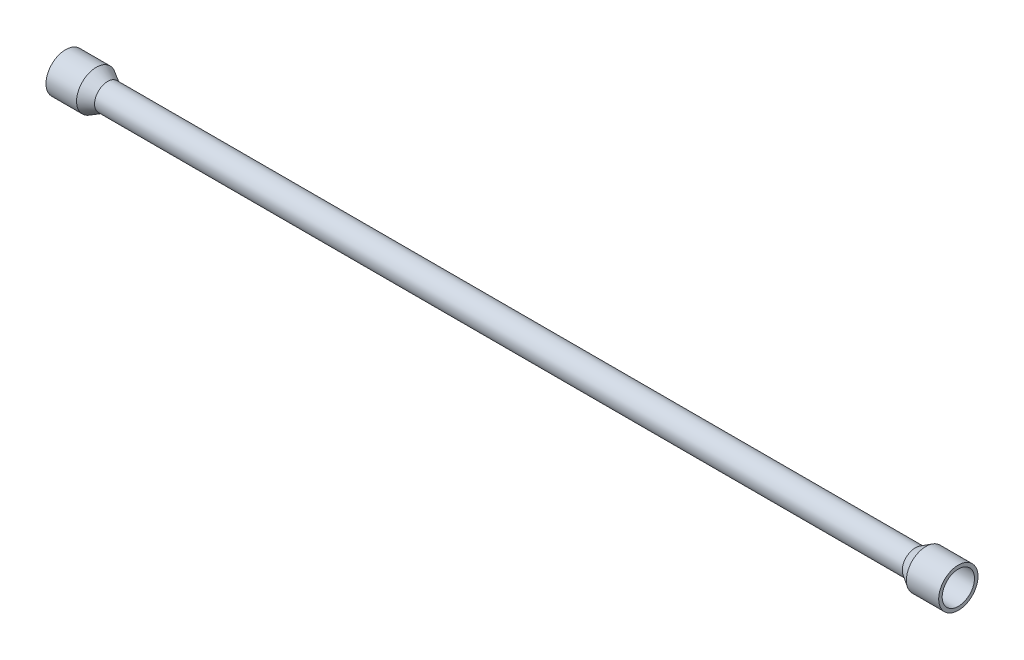
SolidWorks part; units mm, degrees
ref_plane "Front Plane" through (0, 0, 0) normal (0, 0, 1) x (1, 0, 0)
ref_plane "Top Plane" through (0, 0, 0) normal (0, 1, 0) x (1, 0, 0)
ref_plane "Right Plane" through (0, 0, 0) normal (1, 0, 0) x (0, 0, -1)
sketch "Sketch1" plane through (0, 0, 0) normal (1, 0, 0) x (0, 0, -1)
  circle A0 centre (0, 0) radius 75
  circle A1 centre (0, 0) radius 37.5
  dimension "D1" = 150
  dimension "D2" = 75
extrude "Boss-Extrude1" add sketch "Sketch1" along normal blind 4750
sketch "Sketch2" plane through (4750, 0, 0) normal (1, 0, 0) x (0, 0, -1)
  circle A0 centre (0, 0) radius 112.5
  circle A1 centre (0, 0) radius 92.5
  dimension "D1" = 225
  dimension "D2" = 185
extrude "Boss-Extrude2" add sketch "Sketch2" along normal blind 185 separate body
sketch "Sketch4" plane through (0, 0, 0) normal (0, 0, 1) x (1, 0, 0)
  line L0 (4750, 112.5) -> (4688.8349, 75)
  line L1 (4750, 75) -> (0, 75) construction
  line L2 (4688.8349, 75) -> (4750, 75)
  line L3 (4750, 75) -> (4750, 112.5)
  line L4 (5128.6321, 0) -> (4589.2172, 0) construction
revolve "Revolve1" add sketch "Sketch4" angle 360 about L4
sketch "Sketch6" plane through (0, 0, 0) normal (-1, 0, 0) x (0, 0, 1)
  circle A0 centre (0, 0) radius 87.5
  circle A1 centre (0, 0) radius 112.5
  dimension "D1" = 175
  dimension "D2" = 225
extrude "Boss-Extrude3" add sketch "Sketch6" along normal blind 175 separate body
sketch "Sketch7" plane through (0, 0, 0) normal (0, 0, 1) x (1, 0, 0)
  line L0 (0, 0) -> (-301.92, 0) construction
  line L1 (0, 112.5) -> (65.3632, 75)
  line L2 (4688.8349, 75) -> (0, 75) construction
  line L3 (65.3632, 75) -> (0, 75)
  line L4 (0, 75) -> (0, 112.5)
revolve "Revolve2" add sketch "Sketch7" angle 360 about L0
